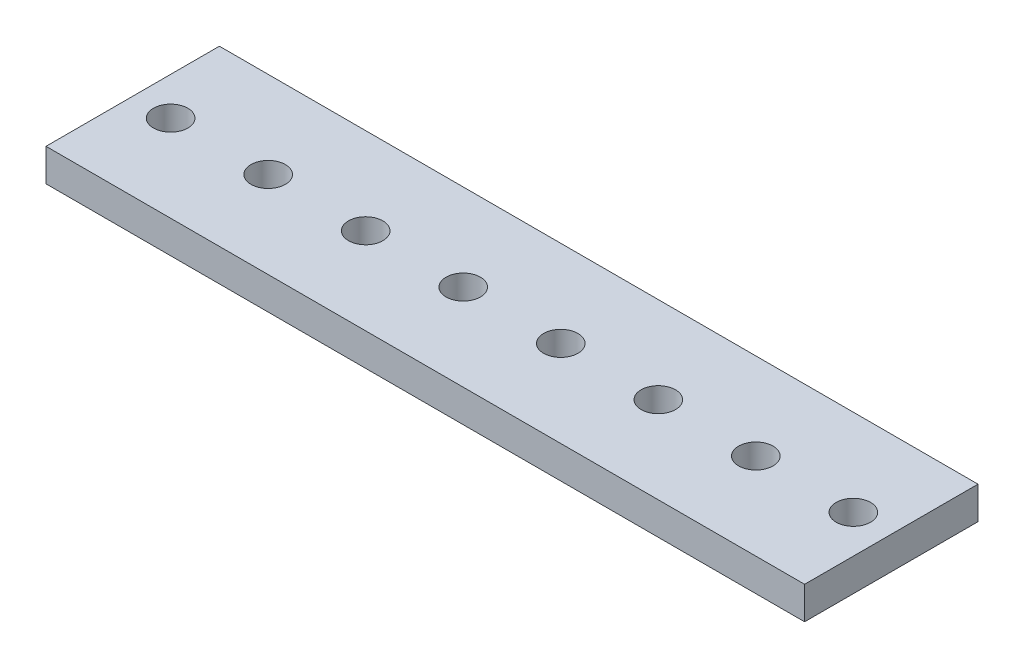
SolidWorks part; units mm, degrees
ref_plane "Front Plane" through (0, 0, 0) normal (0, 0, 1) x (1, 0, 0)
ref_plane "Top Plane" through (0, 0, 0) normal (0, 1, 0) x (1, 0, 0)
ref_plane "Right Plane" through (0, 0, 0) normal (1, 0, 0) x (0, 0, -1)
sketch "Sketch1" plane through (0, 0, 0) normal (0, 1, 0) x (1, 0, 0)
  line L0 (0, 0) -> (0, 22.2718) construction
  line L2 (35, -8) -> (-35, -8)
  line L3 (35, -8) -> (35, 8)
  line L4 (35, 8) -> (-35, 8)
  line L7 (-35, -8) -> (-35, 8)
  line L8 (35, -8) -> (-35, 8) construction
  line L9 (35, 8) -> (-35, -8) construction
  circle A0 centre (0, 0) radius 4.5 construction
  circle A1 centre (-4.5, 0) radius 1.5875
  circle A2 centre (4.5, 0) radius 1.5875
  circle A3 centre (13.5, 0) radius 1.5875
  circle A4 centre (22.5, 0) radius 1.5875
  circle A5 centre (31.5, 0) radius 1.5875
  circle A6 centre (-13.5, 0) radius 1.5875
  circle A7 centre (-22.5, 0) radius 1.5875
  circle A8 centre (-31.5, 0) radius 1.5875
  circle A9 centre (-31.5, 0) radius 9 construction
  circle A10 centre (31.5, 0) radius 9 construction
  circle A11 centre (-31.5, 0) radius 3.175 construction
  circle A12 centre (-22.5, 0) radius 3.175 construction
  circle A13 centre (-13.5, 0) radius 3.175 construction
  circle A14 centre (-4.5, 0) radius 3.175 construction
  circle A15 centre (4.5, 0) radius 3.175 construction
  circle A16 centre (13.5, 0) radius 3.175 construction
  circle A17 centre (22.5, 0) radius 3.175 construction
  circle A18 centre (31.5, 0) radius 3.175 construction
  dimension "D1" = 9
  dimension "D2" = 16
  dimension "D5" = 3.175
  dimension "D6" = 8
  dimension "D7" = 6.35
  dimension "D3" = 70
  dimension "D4" = 4
extrude "Boss-Extrude1" add sketch "Sketch1" along normal blind 3
